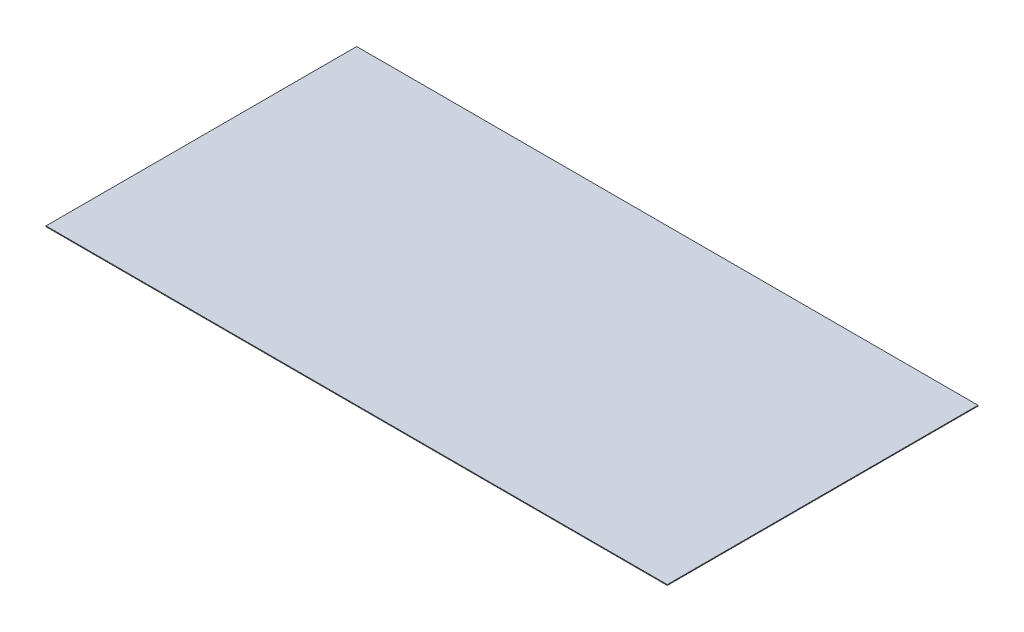
SolidWorks part; units mm, degrees
ref_plane "Front Plane" through (0, 0, 0) normal (0, 0, 1) x (1, 0, 0)
ref_plane "Top Plane" through (0, 0, 0) normal (0, 1, 0) x (1, 0, 0)
ref_plane "Right Plane" through (0, 0, 0) normal (1, 0, 0) x (0, 0, -1)
sketch "Sketch1" plane through (0, 0, 0) normal (0, 1, 0) x (1, 0, 0)
  line L1 (-1220, 610) -> (1220, 610)
  line L2 (-1220, 610) -> (-1220, -610)
  line L3 (-1220, -610) -> (1220, -610)
  line L4 (1220, 610) -> (1220, -610)
  line L5 (-1220, 610) -> (1220, -610) construction
  line L6 (-1220, -610) -> (1220, 610) construction
  point P0 (0, 0)
  dimension "D1" = 2440
  dimension "D2" = 1220
extrude "Boss-Extrude1" add sketch "Sketch1" along normal blind 3
